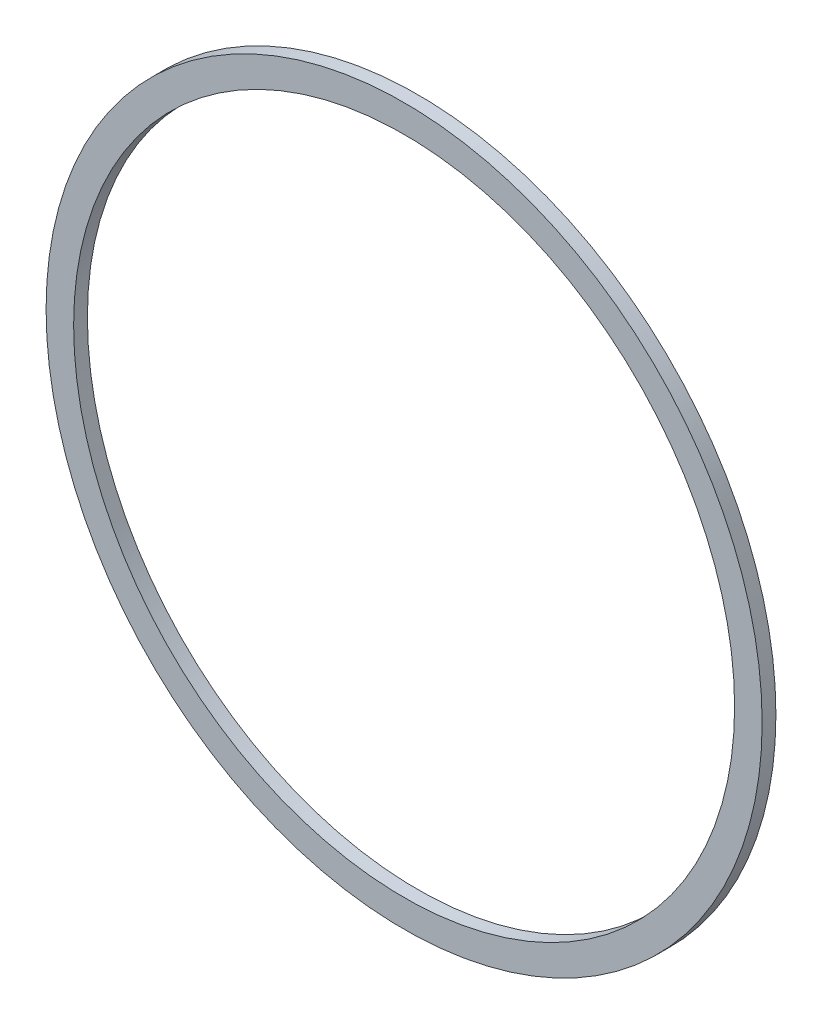
SolidWorks part; units mm, degrees
ref_plane "前视基准面" through (0, 0, 0) normal (0, 0, 1) x (1, 0, 0)
ref_plane "上视基准面" through (0, 0, 0) normal (0, 1, 0) x (1, 0, 0)
ref_plane "右视基准面" through (0, 0, 0) normal (1, 0, 0) x (0, 0, -1)
sketch "草图1" plane through (0, 0, 0) normal (0, 0, 1) x (1, 0, 0)
  circle A0 centre (0, 0) radius 26
  circle A1 centre (0, 0) radius 24
  dimension "D1" = 52
  dimension "D2" = 48
extrude "拉伸1" add sketch "草图1" along normal blind 1
